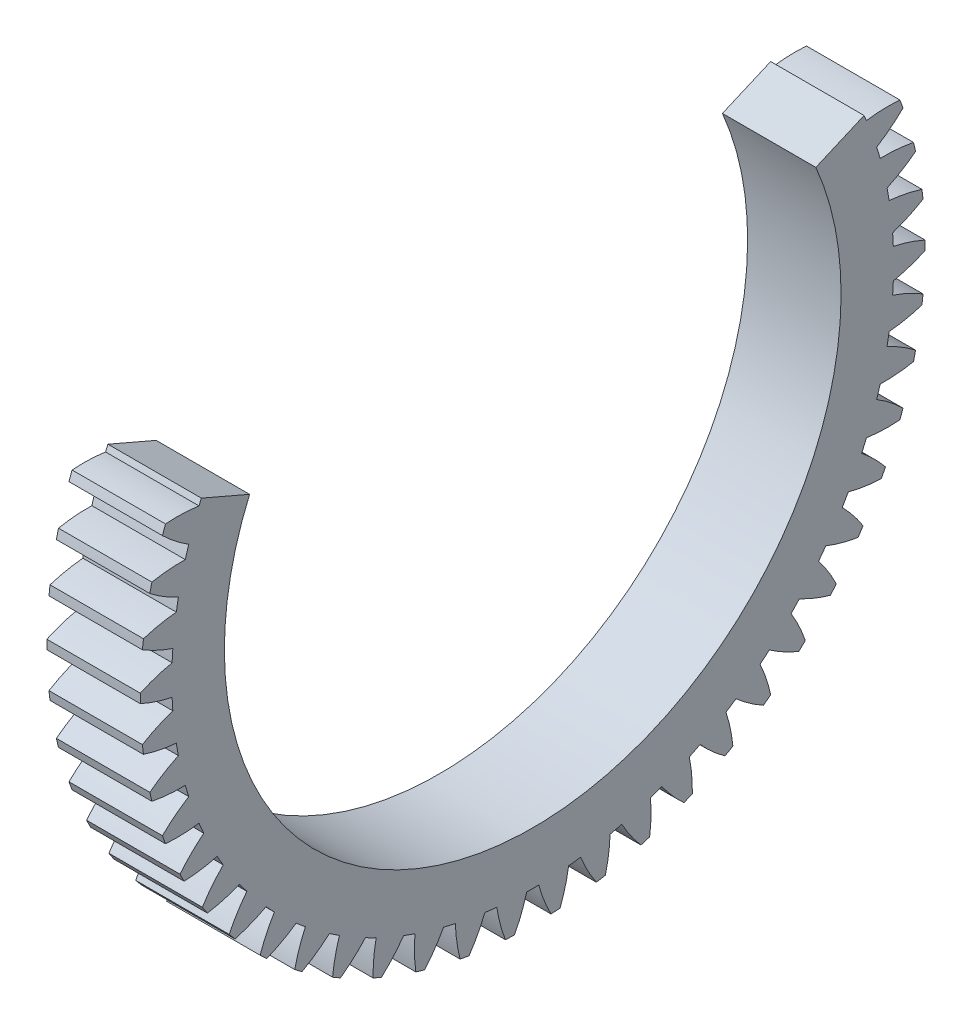
SolidWorks part; units mm, degrees
ref_plane "Plane1" through (0, 0, 0) normal (0, 0, 1) x (1, 0, 0)
ref_plane "Plane2" through (0, 0, 0) normal (0, 1, 0) x (1, 0, 0)
ref_plane "Plane3" through (0, 0, 0) normal (1, 0, 0) x (0, 0, -1)
other "Configuration Table"
sketch "HoldingSke" plane through (0, 0, 0) normal (0, 1, 0) x (1, 0, 0)
  line L0 (0, 0) -> (0.3919, -0.5393)
  line L1 (-15, 0) -> (100, 0) construction
  line L2 (0, 0) -> (-2.1039, 2.3779)
  line L3 (0, 0) -> (-11.863, 4.5341)
  line L4 (0, 0) -> (5.0761, 6.9867)
  line L5 (0, 0) -> (-46.8476, -17.4728)
  line L6 (0, 0) -> (-4.9738, -3.3558)
  line L7 (-2.1039, 2.3779) -> (8.6586, 51.2059)
  line L8 (-76.2, 54.61) -> (-72.9, 54.61)
  line L9 (-71.009, 38.7566) -> (-53.1078, 45.2721)
  line L10 (-76.2, 71.12) -> (104.1128, 71.12)
  line L11 (0, 0) -> (-6, 0)
  line L12 (-76.2, 101.6) -> (-76.147, 101.6)
  line L13 (24.9733, 27.94) -> (52.9518, 28.4284)
  line L14 (24.9733, 27.94) -> (24.9743, 27.94)
  line L15 (24.9733, 27.94) -> (100.4006, 29.5858)
  line L16 (-63.627, -1.5) -> (-12.827, -1.5)
  circle A0 centre (0, 0) radius 21
  circle A1 centre (0, 0) radius 37.5
  circle A2 centre (0, 0) radius 37.5
  circle A3 centre (0, 0) radius 21
  dimension "MHD" = 75
  dimension "Hub_dia" = 75
  dimension "Bore" = 42
  dimension "MBD" = 42
  dimension "Num_teeth" = 54
  dimension "Pitch" = 0.6667
  dimension "Overall_len" = 50
  dimension "Show_teeth" = 54
  dimension "Thickness" = 6
  dimension "OAL" = 50.0001
  dimension "T_dim" = 3.3
  dimension "Ap" = 20
  dimension "H" = 19.05
  dimension "Pitch_radius" = 180.3128
  dimension "Width" = 6
  dimension "Backlash" = 0.053
  dimension "Addendum_fac" = 1
  dimension "Dedendum_fac" = 1.25
  dimension "Clearance_fac" = 0.25
  dimension "Dedendum_add" = 0.001
  dimension "Module" = 1.5
sketch "BasProSke" plane through (0, 0, 0) normal (0, 1, 0) x (1, 0, 0)
  line L0 (-10, 0) -> (60, 0) construction
  line L1 (0, 0) -> (0, 42)
  line L2 (0, 0) -> (10, 0)
  line L3 (10, 0) -> (10, 42)
  line L4 (10, 42) -> (0, 42)
  dimension "Thickness" = 10
  dimension "Diameter" = 84
revolve "Base-Revolve" add sketch "BasProSke" angle 360 about L0
sketch "TooCutSke" plane through (0, 0, 0) normal (1, 0, 0) x (0, 0, -1)
  line L1 (0, 0) -> (0, 107) construction
  line L2 (0, 0) -> (-1.2707, 40.4801) construction
  line L3 (0, 0) -> (-4.708, 80.8339) construction
  line L4 (-1.2707, 40.4801) -> (-2.354, 40.417) construction
  arc A0 (0.645, 38.6186) -> (-0.645, 38.6186) centre (0, 0) ccw
  arc A1 (1.9691, 41.9792) -> (-1.9691, 41.9792) centre (0, 0) ccw
  circle A2 centre (0, 0) radius 40.5 construction
  circle A3 centre (0, 0) radius 38.0576 construction
  arc A4 (-0.645, 38.6186) -> (-1.9691, 41.9792) centre (-16.2853, 34.3972) ccw
  arc A5 (1.9691, 41.9792) -> (0.645, 38.6186) centre (16.2853, 34.3972) ccw
  dimension "Root_dia" = 77.248
  dimension "Overcut_dia" = 84.0508
  dimension "Pitch_dia" = 81
  dimension "Base_dia" = 76.1151
  dimension "Flank_rad" = 16.2
  dimension "Half_ang" = 3.333
  dimension "Half_CT" = 1.0852
extrude "ToothCut" cut sketch "TooCutSke" along normal through all
fillet "Breaks" [suppressed] radius 0.03
fillet "RootFillets" [suppressed] radius 0.376
pattern_circular "TeethCuts" count 54 every 6.667 about axis through (-10, 0, 0) along (1, 0, 0) of "ToothCut", "RootFillets", "Breaks"
sketch "HubNeaOneSke" plane through (0, 0, 0) normal (-1, 0, 0) x (0, 0, 1)
  circle A0 centre (0, 0) radius 37.5
  dimension "Diameter" = 75
extrude "HubNearOne" [suppressed] add sketch "HubNeaOneSke" along normal blind 40.0001
sketch "HubNeaBotSke" plane through (0, 0, 0) normal (-1, 0, 0) x (0, 0, 1)
  circle A0 centre (0, 0) radius 37.5
  dimension "Diameter" = 75
extrude "HubNearBoth" [suppressed] add sketch "HubNeaBotSke" along normal blind 20
ref_plane "FarPln" through (10, 0, 0) normal (1, 0, 0) x (0, 0, -1)
sketch "HubFarSke" plane through (10, 0, 0) normal (1, 0, 0) x (0, 0, -1)
  circle A0 centre (0, 0) radius 37.5
  dimension "Diameter" = 75
extrude "HubFar" [suppressed] add sketch "HubFarSke" along normal blind 20
sketch "BorSke" plane through (0, 0, 0) normal (1, 0, 0) x (0, 0, -1)
  circle A0 centre (0, 0) radius 33
  dimension "Diameter" = 66
extrude "Bore" cut sketch "BorSke" along normal mid plane 100.0001
sketch "KeySke" plane through (0, 0, 0) normal (1, 0, 0) x (0, 0, -1)
  line L0 (-6, 0) -> (-6, 24.3)
  line L1 (-6, 24.3) -> (6, 24.3)
  line L2 (6, 24.3) -> (6, 0)
  line L3 (0, 0) -> (0, 34) construction
  line L4 (-6, 0) -> (6, 0)
  dimension "Offset" = 24.3
  dimension "Width" = 12
extrude "Keyway" [suppressed] cut sketch "KeySke" along normal mid plane 100.0001
pattern_circular "Keyway2" [suppressed] count 2 every 90 about axis through (-10, 0, 0) along (1, 0, 0)
sketch "Sketch1" plane through (0, 0, 0) normal (-1, 0, 0) x (0, 0, 1)
  line L0 (0, 0) -> (0, 43) construction
  line L1 (30.3011, 13.0706) -> (39.4833, 17.0314)
  line L2 (-30.3011, 13.0706) -> (-39.4833, 17.0314)
  line L3 (-30.3011, 13.0706) -> (0, 0) construction
  line L4 (0, 0) -> (30.3011, 13.0706) construction
  arc A0 (-39.4833, 17.0314) -> (39.4833, 17.0314) centre (0, 0) cw
  arc A1 (-30.3011, 13.0706) -> (30.3011, 13.0706) centre (0, 0) cw
  circle A2 centre (0, 0) radius 33 construction
  arc A4 (35.7157, 14.7038) -> (35.2048, 15.8883) centre (0, 0) ccw construction
  arc A5 (-35.2048, 15.8883) -> (-35.7157, 14.7038) centre (0, 0) ccw construction
  point P13 (35.4652, 15.2982)
  point P17 (-35.4652, 15.2982)
  dimension "D1" = 43
extrude "Cut-Extrude1" cut sketch "Sketch1" against normal through all
equation "' \"Module@HoldingSke\" = 6.35"
equation "' \"Num_teeth@HoldingSke\" = 12"
equation "' \"Ap@HoldingSke\" =  20"
equation "' \"Ap@HoldingSke\" = 20"
equation "' \"Width@HoldingSke\" = 0.5 * 25.4"
equation "' \"Hub_dia@HoldingSke\"= 1 * 25.4"
equation "' \"Hub_dia@HoldingSke\" = 1 * 25.4"
equation "' \"Overall_len@HoldingSke\" = 1.0 * 25.4"
equation "' \"Bore@HoldingSke\" = 0.75 * 25.4"
equation "' \"T_dim@HoldingSke\" = 0.1 * 25.4"
equation "' \"Width@KeySke\" = 0.25 * 25.4"
equation "' \"Show_teeth@HoldingSke\" = 13"
equation "' \"Backlash@HoldingSke\" = 0.009 * 25.4"
equation "' \"Addendum_fac@HoldingSke\" = 1.0"
equation "' \"Dedendum_fac@HoldingSke\" = 1.25"
equation "' \"Dedendum_add@HoldingSke\" = 0.00005 * 25.4"
equation "' \"Clearance_fac@HoldingSke\" = 0.25"
equation "\"Pitch@HoldingSke\" = 1 / \"Module@HoldingSke\""
equation "\"Overcut_dia@TooCutSke\" = (\"Num_teeth@HoldingSke\" + 2 * \"Addendum_fac@HoldingSke\") / \"Pitch@HoldingSke\" + 0.002 * 25.4"
equation "\"Pitch_dia@TooCutSke\" = \"Num_teeth@HoldingSke\" / \"Pitch@HoldingSke\""
equation "\"Base_dia@TooCutSke\" = \"Num_teeth@HoldingSke\" / \"Pitch@HoldingSke\" * cos((\"Ap@HoldingSke\"  * 3.14159265 / 180))"
equation "\"Root_dia@TooCutSke\" = (\"Num_teeth@HoldingSke\" + 2) / \"Pitch@HoldingSke\" - 2 * (\"Addendum_fac@HoldingSke\" + \"Dedendum_fac@HoldingSke\") / \"Pitch@HoldingSke\" - \"Dedendum_add@HoldingSke\" * 2"
equation "\"Half_ang@TooCutSke\" = 180 / \"Num_teeth@HoldingSke\""
equation "\"Half_CT@TooCutSke\" = \"Num_teeth@HoldingSke\" / \"Pitch@HoldingSke\" * sin((3.14159265 / 2 / \"Num_teeth@HoldingSke\")) / 2 - 7 * \"Backlash@HoldingSke\" / 4"
equation "\"Flank_rad@TooCutSke\" = \"Num_teeth@HoldingSke\" / \"Pitch@HoldingSke\" / 5"
equation "\"Radius@RootFillets\" = \"Clearance_fac@HoldingSke\" / \"Pitch@HoldingSke\" + \"Dedendum_add@HoldingSke\""
equation "\"Break_rad@Breaks\" = 0.02 / \"Pitch@HoldingSke\""
equation "\"Thickness@HoldingSke\" = \"Width@HoldingSke\""
equation "\"OAL@HoldingSke\" = \"Thickness@HoldingSke\""
equation "\"MHD@HoldingSke\" = (\"Num_teeth@HoldingSke\" + 2) / \"Pitch@HoldingSke\" - 2 * (\"Addendum_fac@HoldingSke\" + \"Dedendum_fac@HoldingSke\")  / \"Pitch@HoldingSke\" - \"Dedendum_add@HoldingSke\" * 2"
equation "\"MBD@HoldingSke\" = (\"Num_teeth@HoldingSke\" + 2) / \"Pitch@HoldingSke\" - 2 * (\"Addendum_fac@HoldingSke\" + \"Dedendum_fac@HoldingSke\")  / \"Pitch@HoldingSke\" - \"Dedendum_add@HoldingSke\" * 2 - 0.002 * 25.4"
equation "\"MHD@HoldingSke\" = ((sgn( \"MHD@HoldingSke\" - \"Hub_dia@HoldingSke\" )-1)*( \"MHD@HoldingSke\" - \"Hub_dia@HoldingSke\" ))/-2+ \"Hub_dia@HoldingSke\""
equation "\"MBD@HoldingSke\" = ((sgn( \"MBD@HoldingSke\" - \"Bore@HoldingSke\" )-1)*( \"MBD@HoldingSke\" - \"Bore@HoldingSke\" ))/-2+ \"Bore@HoldingSke\""
equation "\"OAL@HoldingSke\" = ((sgn( \"OAL@HoldingSke\" - \"Overall_len@HoldingSke\" )+1)*( \"OAL@HoldingSke\" - \"Overall_len@HoldingSke\" ))/2 + \"Overall_len@HoldingSke\" + 0.000002 * 25.4"
equation "\"Num_teeth@TeethCuts\" = int( \"Show_teeth@HoldingSke\" ) + 1"
equation "\"Num_teeth@TeethCuts\" = ((sgn( \"Num_teeth@TeethCuts\" - \"Num_teeth@HoldingSke\" )-1)*( \"Num_teeth@TeethCuts\" - \"Num_teeth@HoldingSke\" ))/-2+ \"Num_teeth@HoldingSke\""
equation "\"Num_teeth@TeethCuts\" = ((sgn( \"Num_teeth@TeethCuts\" - 2.0)+1)*( \"Num_teeth@TeethCuts\" - 2.0))/2 +2.0"
equation "\"Angle@TeethCuts\" = 360.0 / \"Num_teeth@HoldingSke\""
equation "\"Diameter@BasProSke\" = (\"Num_teeth@HoldingSke\" + 2 * \"Addendum_fac@HoldingSke\") / \"Pitch@HoldingSke\""
equation "' \"Fillet_rad@BasProSke\" =  \"Thickness@HoldingSke\" * 0.05"
equation "' \"Fillet_rad@BasProSke\" = \"Thickness@HoldingSke\" * 0.05"
equation "\"MHD@HoldingSke\" = ((sgn( \"MHD@HoldingSke\" - \"Root_dia@TooCutSke\" )-1)*( \"MHD@HoldingSke\" - \"Root_dia@TooCutSke\" ))/-2+ \"Root_dia@TooCutSke\""
equation "\"Diameter@HubNeaOneSke\" = \"MHD@HoldingSke\""
equation "\"Length@HubNearOne\" = \"OAL@HoldingSke\" - \"Thickness@BasProSke\""
equation "\"Diameter@HubNeaBotSke\" = \"MHD@HoldingSke\""
equation "\"Length@HubNearBoth\" = ( \"OAL@HoldingSke\" - \"Thickness@BasProSke\" ) / 2.0"
equation "\"Thickness@FarPln\" = \"Thickness@BasProSke\""
equation "\"Diameter@HubFarSke\" = \"MHD@HoldingSke\""
equation "\"Length@HubFar\" = ( \"OAL@HoldingSke\" - \"Thickness@BasProSke\" ) / 2.0"
equation "\"D1@Bore\" = \"OAL@HoldingSke\" * 2.0"
equation "\"D1@Keyway\" = \"OAL@HoldingSke\" * 2.0"
equation "\"Offset@KeySke\" = \"T_dim@HoldingSke\" + \"MBD@HoldingSke\" / 2.0"
